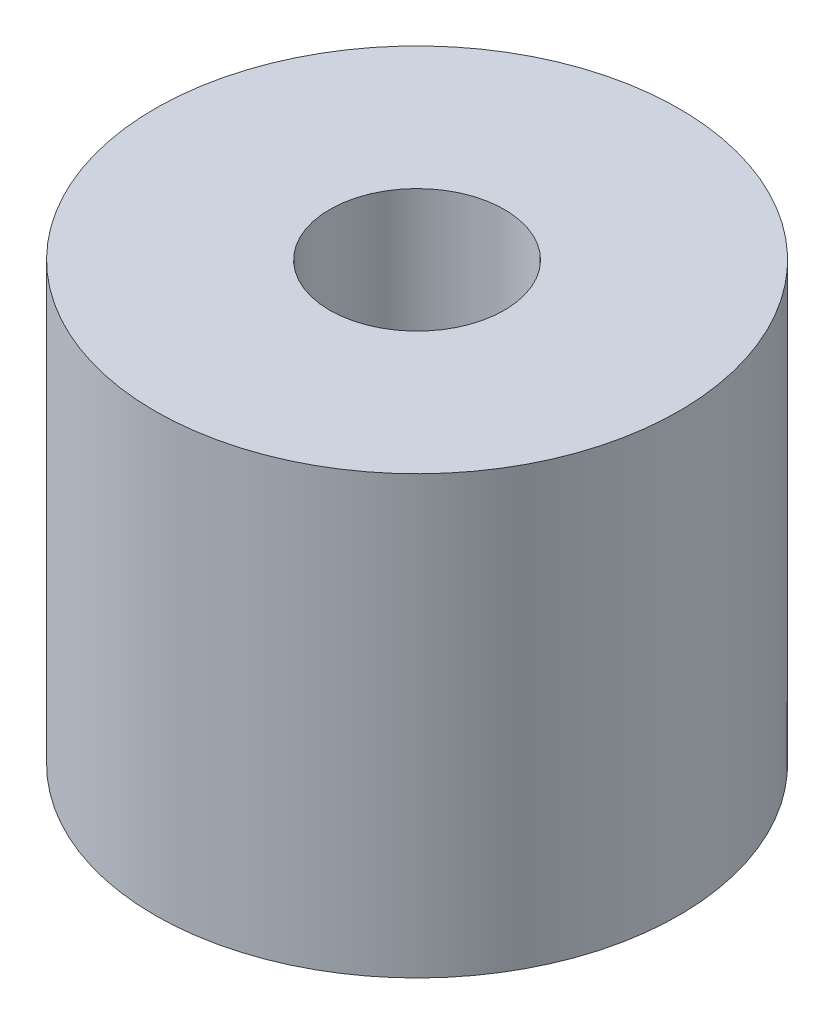
SolidWorks part; units mm, degrees
ref_plane "Спереди" through (0, 0, 0) normal (0, 0, 1) x (1, 0, 0)
ref_plane "Сверху" through (0, 0, 0) normal (0, 1, 0) x (1, 0, 0)
ref_plane "Справа" through (0, 0, 0) normal (1, 0, 0) x (0, 0, -1)
sketch "Эскиз1" plane through (0, 0, 0) normal (0, 1, 0) x (1, 0, 0)
  circle A0 centre (0, 0) radius 5
  circle A1 centre (0, 0) radius 15
extrude "Вытянуть1" add sketch "Эскиз1" along normal blind 25
